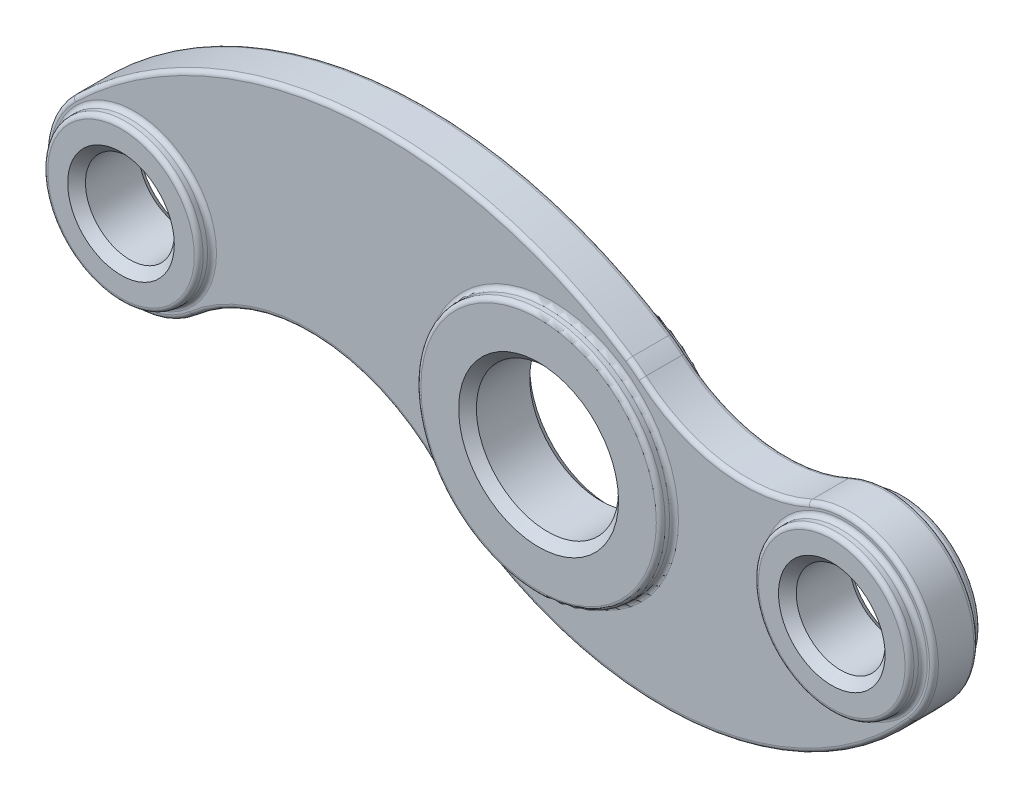
SolidWorks part; units mm, degrees
ref_plane "前视基准面" through (0, 0, 0) normal (0, 0, 1) x (1, 0, 0)
ref_plane "上视基准面" through (0, 0, 0) normal (0, 1, 0) x (1, 0, 0)
ref_plane "右视基准面" through (0, 0, 0) normal (1, 0, 0) x (0, 0, -1)
other "Configuration Table"
sketch "草图1" plane through (0, 0, 0) normal (0, 0, 1) x (1, 0, 0)
  arc A0 (-13.9295, 14.3516) -> (13.1117, -15.1024) centre (0, 0) ccw
  arc A1 (114.2361, 23.484) -> (111.1991, 25.7913) centre (94, 0) ccw
  arc A2 (175, -13.2288) -> (151.6667, 18.1812) centre (160, 0) ccw
  arc A3 (114.2361, 23.484) -> (151.6667, 18.1812) centre (137.0833, 49.9983) ccw
  arc A4 (76.5625, -25.6307) -> (175, -13.2288) centre (118.75, 36.3791) ccw
  arc A5 (70.1322, -19.7821) -> (13.1117, -15.1024) centre (39.3351, -45.3073) ccw
  arc A7 (70.1322, -19.7821) -> (76.5625, -25.6307) centre (94, 0) ccw
  arc A8 (111.1991, 25.7913) -> (-13.9295, 14.3516) centre (55.7181, -57.4064) ccw
  dimension "D3" = 40
  dimension "D4" = 62
  dimension "D5" = 40
  dimension "D6" = 35
  dimension "D7" = 75
  dimension "D8" = 40
  dimension "D9" = 100
  dimension "D1" = 94
  dimension "D2" = 66
extrude "凸台-拉伸1" add sketch "草图1" along normal mid plane 10
sketch "草图3" plane through (0, 0, 0) normal (0, 0, 1) x (1, 0, 0)
  circle A0 centre (0, 0) radius 17.5
  circle A1 centre (94, 0) radius 27.5
  circle A2 centre (160, 0) radius 17.5
  dimension "D3" = 35
  dimension "D4" = 55
  dimension "D5" = 35
  dimension "D1" = 94
  dimension "D2" = 66
extrude "凸台-拉伸2" add sketch "草图3" along normal mid plane 16
sketch "草图4" plane through (0, 0, 0) normal (0, 0, 1) x (1, 0, 0)
  circle A0 centre (0, 0) radius 10
  circle A1 centre (94, 0) radius 16
  circle A2 centre (160, 0) radius 10
  circle A3 centre (94, 0) radius 27.5 construction
  circle A4 centre (160, 0) radius 17.5 construction
  dimension "D1" = 20
  dimension "D2" = 32
  dimension "D3" = 20
extrude "切除-拉伸1" cut sketch "草图4" against normal mid plane 16
fillet "圆角1" radius 1 28 edges at (112.7531, 24.6844, -5) (46.6137, 42.1783, -5) (-14.7327, -13.5258, -5) (42.6069, -5.4413, -5) (73.1414, -22.9329, -5) (128.125, -38.0327, -5) (176.0548, 11.9266, -5) (132.1739, 15.3443, -5) (17.5, 0, -5) (121.5, 0, -5) (177.5, 0, -5) (176.0548, 11.9266, 5) (128.125, -38.0327, 5) (73.1414, -22.9329, 5) (42.6069, -5.4413, 5) (-14.7327, -13.5258, 5) (46.6137, 42.1783, 5) (112.7531, 24.6844, 5) (132.1739, 15.3443, 5) (17.5, 0, 5) (121.5, 0, 5) (177.5, 0, 5) (17.5, 0, 8) (177.5, 0, 8) (121.5, 0, 8) (17.5, 0, -8) (121.5, 0, -8) (177.5, 0, -8)
chamfer "倒角1" distance 2 6 edges at (10, 0, 8) (10, 0, -8) (110, 0, 8) (110, 0, -8) (170, 0, 8) (170, 0, -8)
